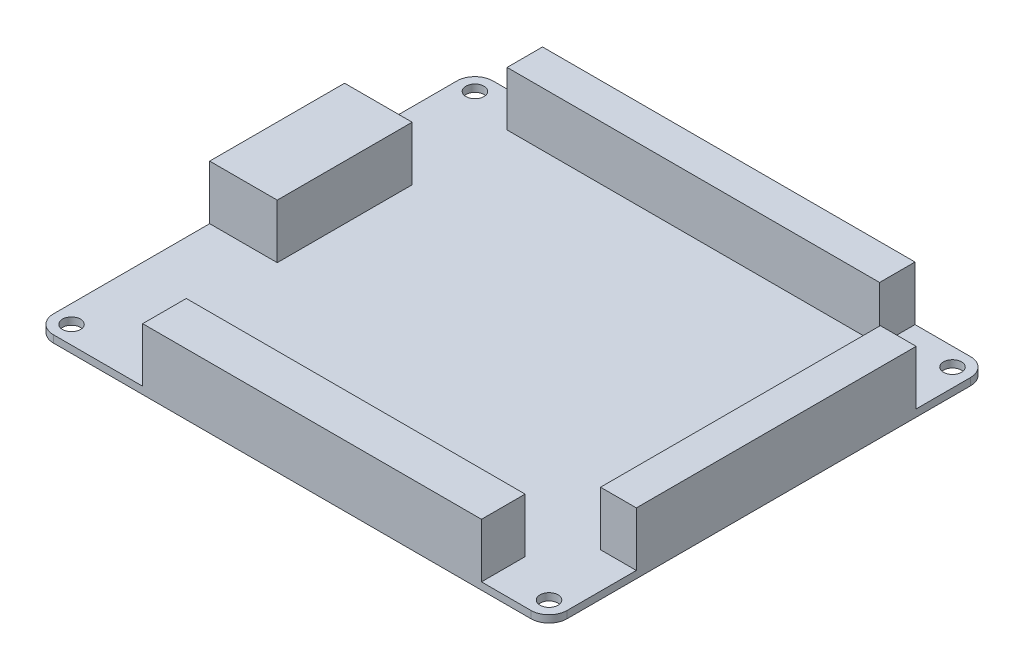
SolidWorks part; units mm, degrees
ref_plane "前视基准面" through (0, 0, 0) normal (0, 0, 1) x (1, 0, 0)
ref_plane "上视基准面" through (0, 0, 0) normal (0, 1, 0) x (1, 0, 0)
ref_plane "右视基准面" through (0, 0, 0) normal (1, 0, 0) x (0, 0, -1)
other "Configuration Table"
sketch "草图1" plane through (0, 0, 0) normal (0, 1, 0) x (1, 0, 0)
  line L1 (39.65, -36.5) -> (-39.65, -36.5)
  line L2 (42.65, -33.5) -> (42.65, 33.5)
  line L3 (39.65, 36.5) -> (-39.65, 36.5)
  line L4 (-42.65, -33.5) -> (-42.65, 33.5)
  line L5 (42.65, -36.5) -> (-42.65, 36.5) construction
  line L6 (42.65, 36.5) -> (-42.65, -36.5) construction
  arc A0 (42.65, 33.5) -> (39.65, 36.5) centre (39.65, 33.5) ccw
  arc A1 (39.65, -36.5) -> (42.65, -33.5) centre (39.65, -33.5) ccw
  arc A2 (-39.65, -36.5) -> (-42.65, -33.5) centre (-39.65, -33.5) cw
  arc A3 (-39.65, 36.5) -> (-42.65, 33.5) centre (-39.65, 33.5) ccw
  circle A5 centre (39.65, 33.5) radius 1.5
  circle A6 centre (-39.65, 33.5) radius 1.5
  circle A7 centre (-39.65, -33.5) radius 1.5
  circle A8 centre (39.65, -33.5) radius 1.5
  point P0 (0, 0)
  dimension "D3" = 3
  dimension "D4" = 3
  dimension "D5" = 3
  dimension "D6" = 3
  dimension "D7" = 3
  dimension "D1" = 85.3
  dimension "D2" = 73
extrude "凸台-拉伸1" add sketch "草图1" along normal blind 1.2 contours L3 A3 L4 A2 L1 A1 L2 A0 A8 A7 A6 A5
sketch "草图2" plane through (0, 1.2, 0) normal (0, 1, 0) x (1, 0, 0)
  line L0 (39.65, -36.5) -> (-39.65, -36.5) construction
  line L1 (-24.8333, -36.5) -> (31.4318, -36.5)
  line L2 (-24.8333, -36.5) -> (-24.8333, -29.2535)
  line L3 (-24.8333, -29.2535) -> (31.4318, -29.2535)
  line L4 (31.4318, -36.5) -> (31.4318, -29.2535)
  line L5 (42.65, -33.5) -> (42.65, 33.5) construction
  line L6 (42.65, -22.0023) -> (36.7031, -22.0023)
  line L7 (42.65, -22.0023) -> (42.65, 24.4645)
  line L8 (42.65, 24.4645) -> (36.7031, 24.4645)
  line L9 (36.7031, -22.0023) -> (36.7031, 24.4645)
  line L10 (39.65, 36.5) -> (-39.65, 36.5) construction
  line L11 (30.4283, 36.5) -> (-31.4295, 36.5)
  line L12 (30.4283, 36.5) -> (30.4283, 30.6142)
  line L13 (30.4283, 30.6142) -> (-31.4295, 30.6142)
  line L14 (-31.4295, 36.5) -> (-31.4295, 30.6142)
  line L15 (-42.65, -33.5) -> (-42.65, 33.5) construction
  line L16 (-42.65, -7.5566) -> (-31.4295, -7.5566)
  line L17 (-42.65, -7.5566) -> (-42.65, 14.849)
  line L18 (-42.65, 14.849) -> (-31.4295, 14.849)
  line L19 (-31.4295, -7.5566) -> (-31.4295, 14.849)
extrude "凸台-拉伸2" add sketch "草图2" along normal blind 9
